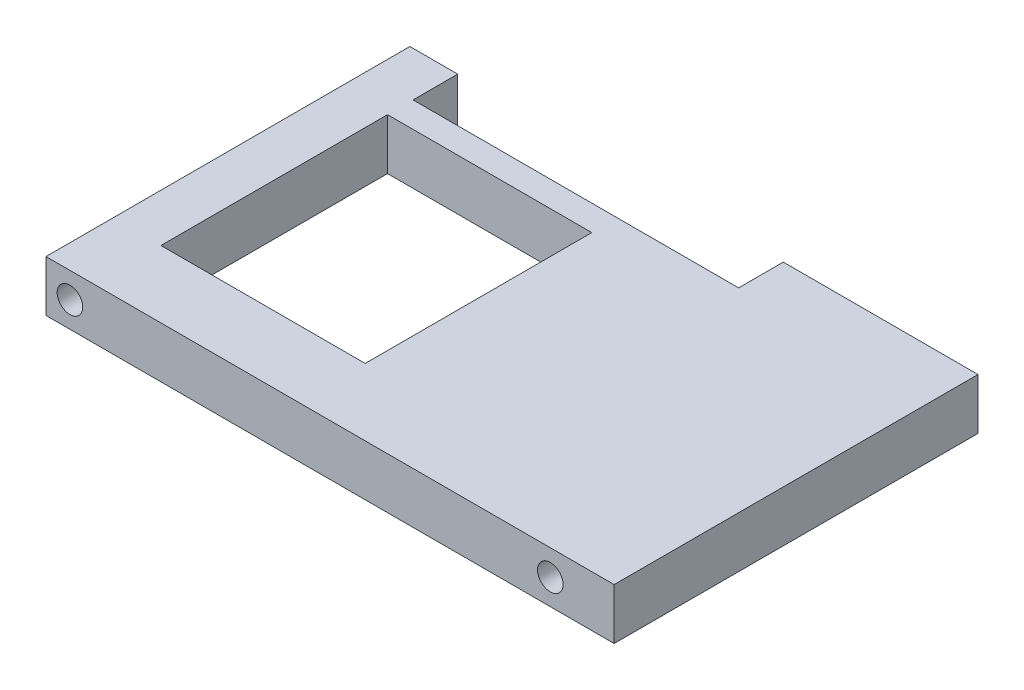
SolidWorks part; units mm, degrees
ref_plane "Front Plane" through (0, 0, 0) normal (0, 0, 1) x (1, 0, 0)
ref_plane "Top Plane" through (0, 0, 0) normal (0, 1, 0) x (1, 0, 0)
ref_plane "Right Plane" through (0, 0, 0) normal (1, 0, 0) x (0, 0, -1)
sketch "Sketch1" plane through (0, 0, 0) normal (0, 1, 0) x (1, 0, 0)
  line L1 (0, 0) -> (89, 0)
  line L2 (0, 0) -> (0, 57)
  line L3 (0, 57) -> (89, 57)
  line L4 (89, 0) -> (89, 57)
  dimension "D1" = 89
  dimension "D2" = 57
extrude "Boss-Extrude1" add sketch "Sketch1" along normal blind 8 contours L1 L4 L3 L2
sketch "Sketch2" plane through (0, 8, 0) normal (0, 1, 0) x (1, 0, 0)
  line L2 (7.5, 0) -> (7.5, 57)
  line L3 (7.5, 0) -> (7.5, 57)
  line L5 (39.5, 0) -> (39.5, 57)
  line L6 (39.5, 0) -> (39.5, 57)
  line L8 (0, 10.5) -> (89, 10.5)
  line L9 (0, 10.5) -> (89, 10.5)
  line L11 (0, 46) -> (89, 46)
  line L12 (0, 46) -> (89, 46)
  line L14 (0, 50) -> (89, 50)
  line L15 (0, 50) -> (89, 50)
  line L17 (0, 56) -> (89, 56)
  line L18 (0, 56) -> (89, 56)
  line L22 (58.5, 0) -> (58.5, 57)
  line L23 (58.5, 0) -> (58.5, 57)
  line M12 (89, 57) -> (0, 57)
  dimension "D1" = 7.5
  dimension "D2" = 39.5
  dimension "D3" = 10.5
  dimension "D4" = 11
  dimension "D5" = 7
  dimension "D6" = 1
  dimension "D7" = 58.5
extrude "Cut-Extrude2" cut sketch "Sketch2" against normal through all contours L12 L3 L9 L6 | L18 L3 L15 L6 | L15 L23 L18 L6 | L18 L23 L6 M12 | L3 L18 L6 M12
sketch "Sketch3" plane through (0, 0, 0) normal (0, 0, 1) x (1, 0, 0)
  line L0 (0, 4) -> (89, 4) construction
  line L1 (0, 8) -> (0, 0) construction
  line L2 (89, 8) -> (89, 0) construction
  circle A0 centre (3.75, 4) radius 2
  circle A1 centre (79, 4) radius 2
  dimension "D1" = 3.75
  dimension "D3" = 4
  dimension "D4" = 4
  dimension "D2" = 10
extrude "Cut-Extrude3" cut sketch "Sketch3" against normal blind 6.7
ref_plane "Plane1" through (0, 0, -28.5) normal (0, 0, 1) x (1, 0, 0)
mirror "Mirror1" about plane through (0, 0, -28.5) normal (0, 0, 1) of "Cut-Extrude3"
